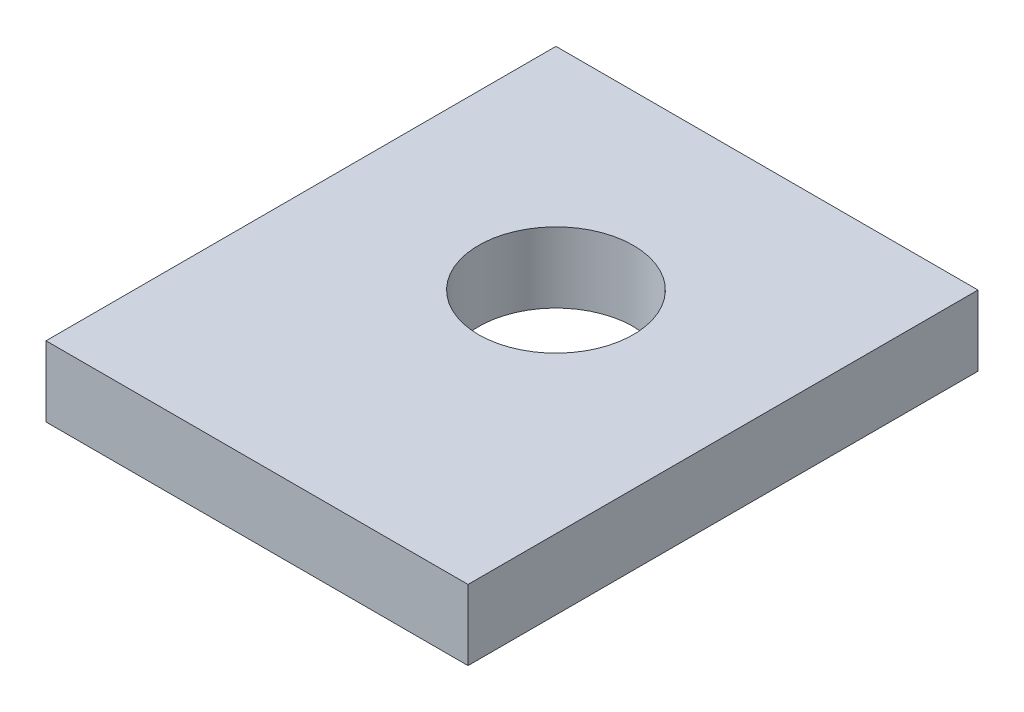
SolidWorks part; units mm, degrees
other "Encoder Board Edge Clamp 1"
ref_plane "Front Plane" through (0, 0, 0) normal (0, 0, 1) x (1, 0, 0)
ref_plane "Top Plane" through (0, 0, 0) normal (0, 1, 0) x (1, 0, 0)
ref_plane "Right Plane" through (0, 0, 0) normal (1, 0, 0) x (0, 0, -1)
sketch3d "Main Profile Sketch datum points"
  point P0 (0, -203.2, 0)
  point P1 (10, -203.2, 0)
  point P2 (0, -203.2, 10)
ref_plane "Main Profile Sketch plane" through (0, -203.2, 0) normal (0, -1, 0) x (-1, 0, 0)
sketch "Main Profile Sketch" plane through (0, -203.2, 0) normal (0, -1, 0) x (-1, 0, 0)
  line L0 (16.0092, 70.7449) -> (22.0092, 70.7449)
  line L1 (16.0092, 70.7449) -> (16.0092, 63.4949)
  line L2 (16.0092, 63.4949) -> (22.0092, 63.4949)
  line L3 (22.0092, 70.7449) -> (22.0092, 63.4949)
  circle A0 centre (19.0092, 67.7449) radius 1.1
extrude "Main Extrusion" add sketch "Main Profile Sketch" along normal blind 1 separate body
